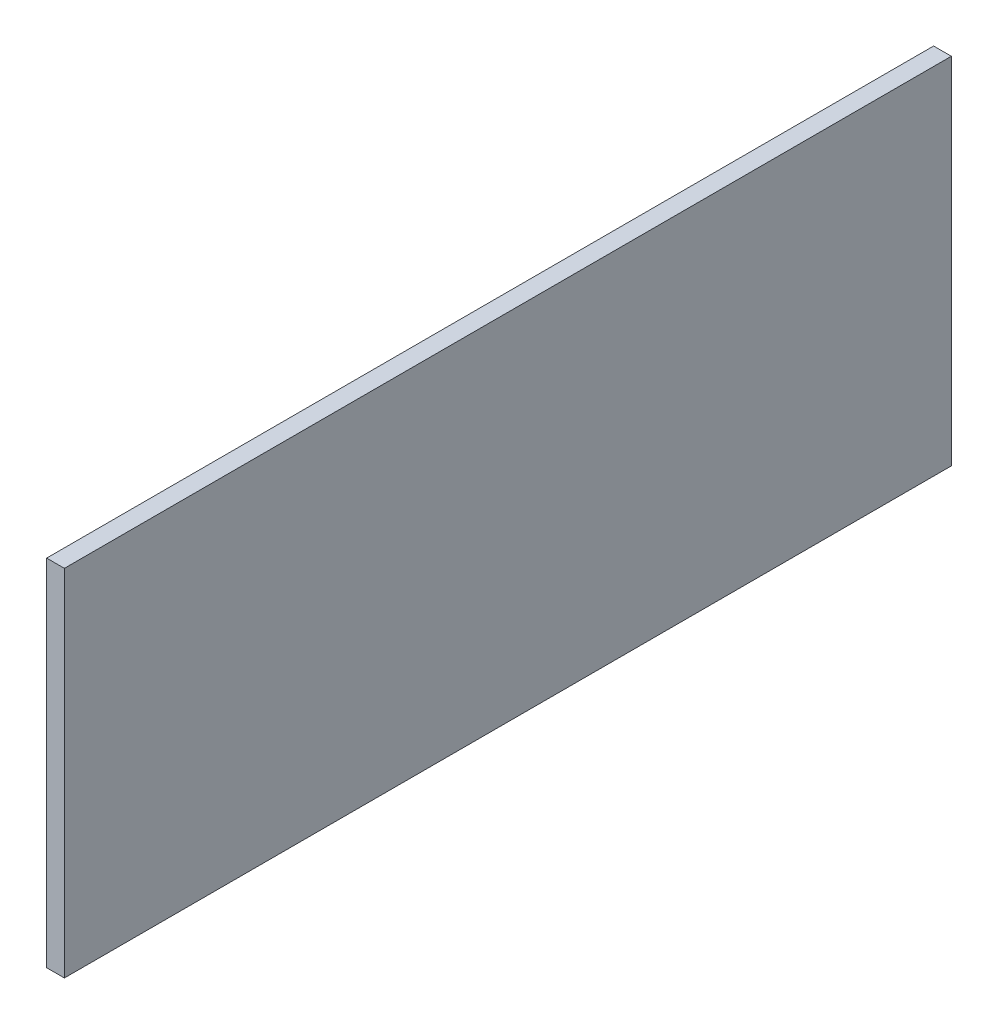
SolidWorks part; units mm, degrees
ref_plane "Front Plane" through (0, 0, 0) normal (0, 0, 1) x (1, 0, 0)
ref_plane "Top Plane" through (0, 0, 0) normal (0, 1, 0) x (1, 0, 0)
ref_plane "Right Plane" through (0, 0, 0) normal (1, 0, 0) x (0, 0, -1)
sketch "Sketch1" plane through (0, 0, 0) normal (1, 0, 0) x (0, 0, -1)
  line L1 (50, -20) -> (-50, -20)
  line L2 (50, -20) -> (50, 20)
  line L3 (50, 20) -> (-50, 20)
  line L4 (-50, -20) -> (-50, 20)
  line L5 (50, -20) -> (-50, 20) construction
  line L6 (50, 20) -> (-50, -20) construction
  point P0 (0, 0)
  dimension "D1" = 100
  dimension "D2" = 40
extrude "Boss-Extrude1" add sketch "Sketch1" along normal blind 2
